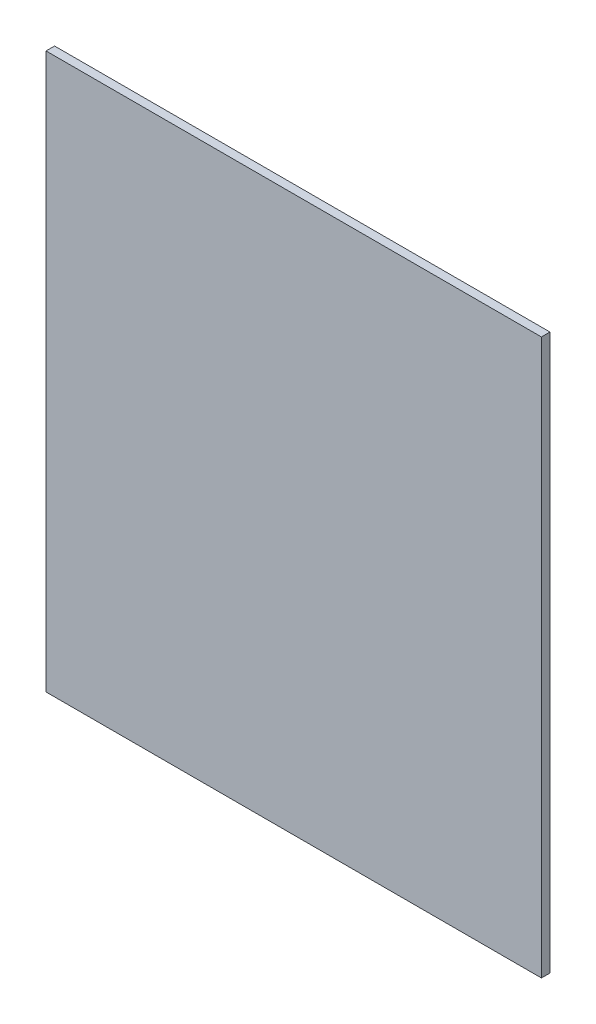
SolidWorks part; units mm, degrees
ref_plane "Plan de face" through (0, 0, 0) normal (0, 0, 1) x (1, 0, 0)
ref_plane "Plan de dessus" through (0, 0, 0) normal (0, 1, 0) x (1, 0, 0)
ref_plane "Plan de droite" through (0, 0, 0) normal (1, 0, 0) x (0, 0, -1)
sketch "Esquisse1" plane through (0, 0, 0) normal (0, 0, 1) x (1, 0, 0)
  line L1 (0, 0) -> (116, 0)
  line L2 (0, 0) -> (0, 130)
  line L3 (0, 130) -> (116, 130)
  line L4 (116, 0) -> (116, 130)
  dimension "D1" = 130
  dimension "D2" = 116
extrude "Boss.-Extru.1" add sketch "Esquisse1" along normal blind 2
